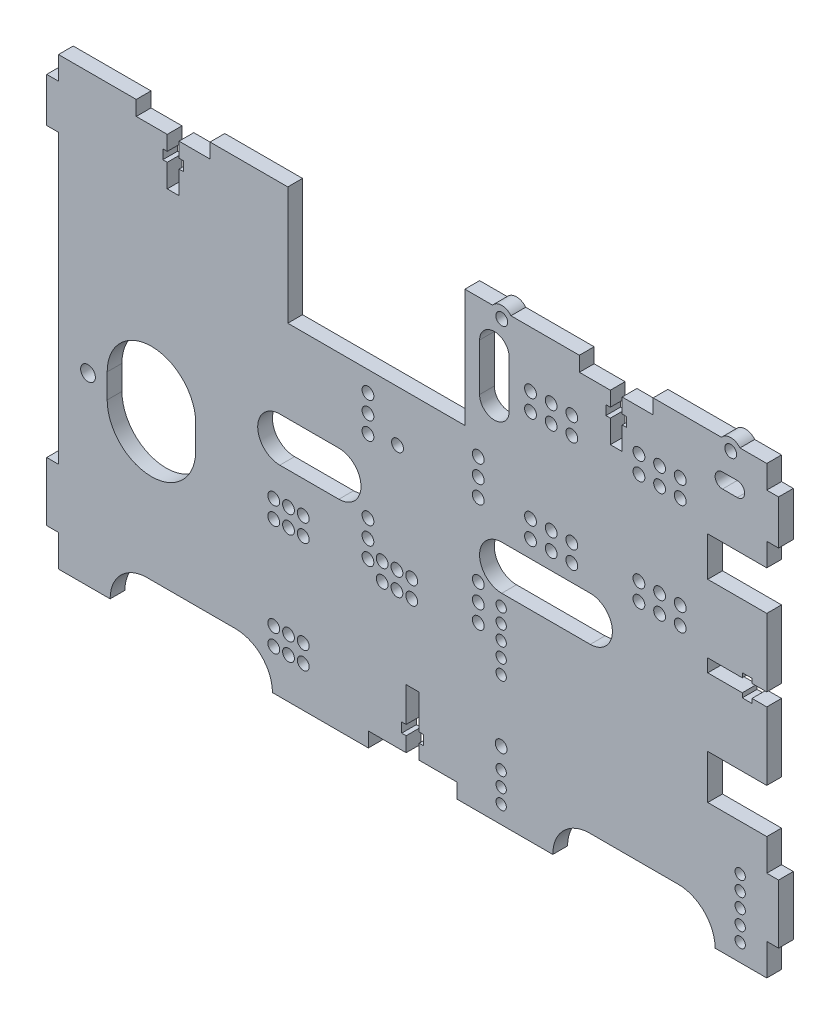
SolidWorks part; units mm, degrees
ref_plane "Front Plane" through (0, 0, 0) normal (0, 0, 1) x (1, 0, 0)
ref_plane "Top Plane" through (0, 0, 0) normal (0, 1, 0) x (1, 0, 0)
ref_plane "Right Plane" through (0, 0, 0) normal (1, 0, 0) x (0, 0, -1)
sketch "Sketch1" plane through (0, 0, 0) normal (0, 0, 1) x (1, 0, 0)
  line L1 (-120, 75.5) -> (120, 75.5)
  line L2 (-120, 75.5) -> (-120, -75.5)
  line L3 (-120, -75.5) -> (120, -75.5)
  line L4 (120, 75.5) -> (120, -75.5)
  dimension "D1" = 240
  dimension "D2" = 120
  dimension "D3" = 151
  dimension "D4" = 75.5
extrude "Boss-Extrude1" add sketch "Sketch1" along normal blind 5
sketch "Sketch2" plane through (0, 0, 0) normal (0, 0, -1) x (-1, 0, 0)
  line L1 (42.3015, 35.5) -> (42.3015, 75.5)
  line L3 (-17.6985, 75.5) -> (-17.6985, 35.5)
  line L4 (-120, 75.5) -> (120, 75.5) construction
  line L5 (42.3015, 35.5) -> (-17.6985, 35.5)
  line L6 (42.3015, 75.5) -> (-17.6985, 75.5)
  line L7 (-120, -75.5) -> (-120, 75.5) construction
  dimension "D1" = 60
  dimension "D2" = 102.3015
extrude "Cut-Extrude1" cut sketch "Sketch2" against normal blind 5
sketch "Sketch4" plane through (0, 0, 0) normal (0, 0, -1) x (-1, 0, 0)
  circle A0 centre (-107.8, 73) radius 2
  circle A1 centre (-30.2, 73) radius 2
  dimension "D1" = 4
  dimension "D2" = 4
extrude "Cut-Extrude3" cut sketch "Sketch4" against normal blind 5
sketch "Sketch5" plane through (0, 0, 0) normal (0, 0, -1) x (-1, 0, 0)
  circle A0 centre (-30.2, 73) radius 2
  circle A1 centre (-107.8, 73) radius 2
  circle A2 centre (-30.2, 73) radius 4
  circle A3 centre (-107.8, 73) radius 4
  dimension "D1" = 8
  dimension "D2" = 8
extrude "Boss-Extrude2" add sketch "Sketch5" against normal blind 5
sketch "Sketch6" plane through (0, 0, 0) normal (0, 0, -1) x (-1, 0, 0)
  circle A0 centre (117.5, 7.7) radius 2
  circle A1 centre (117.5, 63.3) radius 2
  dimension "D1" = 4
  dimension "D2" = 4
extrude "Cut-Extrude4" [suppressed] cut sketch "Sketch6" against normal blind 5
sketch "Sketch7" [suppressed] plane through (0, 0, 0) normal (0, 0, -1) x (-1, 0, 0)
  circle A0 centre (117.5, 7.7) radius 2
  circle A1 centre (117.5, 63.3) radius 1.9875
  circle A2 centre (117.5, 7.7) radius 4
  circle A3 centre (117.5, 63.3) radius 4
  dimension "D1" = 8
  dimension "D2" = 8
extrude "Boss-Extrude3" [suppressed] add sketch "Sketch7" against normal blind 5
sketch "Sketch8" plane through (0, 0, 0) normal (0, 0, -1) x (-1, 0, 0)
  line L0 (105, -60.5) -> (105, -40.5) construction
  line L1 (100, -60.5) -> (100, -40.5)
  line L2 (110, -60.5) -> (110, -40.5)
  line L3 (120, -75.5) -> (-120, -75.5) construction
  line L4 (120, 75.5) -> (120, -75.5) construction
  line L5 (0, 0) -> (0, -55.5387) construction
  arc A0 (100, -60.5) -> (110, -60.5) centre (105, -60.5) ccw
  arc A1 (110, -40.5) -> (100, -40.5) centre (105, -40.5) ccw
  point P2 (105, -50.5)
  point P17 (-92, -45.5)
  dimension "D1" = 20
  dimension "D2" = 15
  dimension "D3" = 10
  dimension "D4" = 10
extrude "Cut-Extrude5" [suppressed] cut sketch "Sketch8" against normal blind 5
sketch "Sketch9" plane through (0, 0, 0) normal (0, 0, -1) x (-1, 0, 0)
  circle A0 centre (117.5, 44.8) radius 2
  circle A1 centre (117.5, -10.8) radius 2
  dimension "D1" = 4
  dimension "D2" = 4
extrude "Cut-Extrude6" [suppressed] cut sketch "Sketch9" against normal blind 5
sketch "Sketch10" [suppressed] plane through (0, 0, 0) normal (0, 0, -1) x (-1, 0, 0)
  circle A0 centre (117.5, -10.8) radius 2
  circle A1 centre (117.5, -10.8) radius 4
  circle A2 centre (117.5, 44.8) radius 2
  circle A3 centre (117.5, 44.8) radius 4
  dimension "D1" = 8
  dimension "D2" = 8
extrude "Boss-Extrude4" [suppressed] add sketch "Sketch10" against normal blind 5
sketch "Sketch12" plane through (0, 0, 0) normal (0, 0, -1) x (-1, 0, 0)
  circle A0 centre (-28.1604, -53.4404) radius 2
  dimension "D1" = 4
extrude "Cut-Extrude7" [suppressed] cut sketch "Sketch12" against normal blind 5
sketch "Sketch13" plane through (0, 0, 0) normal (0, 0, -1) x (-1, 0, 0)
  circle A1 centre (110, -13) radius 2.5
extrude "Cut-Extrude8" cut sketch "Sketch13" against normal blind 10
sketch "Sketch14" plane through (0, 0, 0) normal (0, 0, -1) x (-1, 0, 0)
  line L0 (-104.6775, 75.5) -> (-33.3225, 75.5) construction
  line L1 (-120, -75.5) -> (-120, 75.5) construction
  line L2 (120, -75.5) -> (-120, -75.5) construction
  line L3 (120, 75.5) -> (120, -75.5) construction
  line L4 (42.3015, 75.5) -> (120, 75.5) construction
  circle A0 centre (-105, -60.5) radius 2.5
  circle A1 centre (105, -60.5) radius 2.5
  circle A2 centre (-105, 60.5) radius 2.5
  circle A3 centre (105, 60.5) radius 2.5
  dimension "D1" = 5
  dimension "D2" = 5
  dimension "D3" = 5
  dimension "D4" = 5
  dimension "D5" = 15
  dimension "D6" = 15
  dimension "D7" = 15
  dimension "D8" = 15
  dimension "D9" = 15
  dimension "D10" = 15
  dimension "D11" = 15
  dimension "D12" = 15
extrude "Cut-Extrude9" [suppressed] cut sketch "Sketch14" against normal blind 10
sketch "Sketch15" plane through (0, 0, 0) normal (0, 0, -1) x (-1, 0, 0)
  line L0 (-70, 0) -> (-50, 0) construction
  line L1 (-70, 7.5) -> (-50, 7.5)
  line L2 (-70, -7.5) -> (-50, -7.5)
  line L3 (50, 0) -> (70, 0) construction
  line L4 (50, 7.5) -> (70, 7.5)
  line L5 (50, -7.5) -> (70, -7.5)
  line L6 (-102.5, 55.5) -> (-102.5, 35.5) construction
  line L7 (-95, 55.5) -> (-95, 35.5)
  line L8 (-110, 55.5) -> (-110, 35.5)
  line L9 (-104.6775, 75.5) -> (-33.3225, 75.5) construction
  line L10 (-120, -75.5) -> (-120, 75.5) construction
  line L11 (0, 0) -> (0, 86.6929) construction
  line L12 (102.5, 55.5) -> (102.5, 35.5) construction
  line L13 (95, 55.5) -> (95, 35.5)
  line L14 (110, 55.5) -> (110, 35.5)
  arc A0 (-70, 7.5) -> (-70, -7.5) centre (-70, 0) ccw
  arc A1 (-50, -7.5) -> (-50, 7.5) centre (-50, 0) ccw
  arc A2 (50, 7.5) -> (50, -7.5) centre (50, 0) ccw
  arc A3 (70, -7.5) -> (70, 7.5) centre (70, 0) ccw
  arc A4 (-95, 55.5) -> (-110, 55.5) centre (-102.5, 55.5) ccw
  arc A5 (-110, 35.5) -> (-95, 35.5) centre (-102.5, 35.5) ccw
  arc A6 (95, 55.5) -> (110, 55.5) centre (102.5, 55.5) cw
  arc A7 (110, 35.5) -> (95, 35.5) centre (102.5, 35.5) cw
  point P2 (-60, 0)
  point P7 (60, 0)
  point P14 (-60, 7.5)
  point P15 (60, -7.5)
  point P16 (-102.5, 45.5)
  point P32 (102.5, 45.5)
  dimension "D1" = 20
  dimension "D2" = 20
  dimension "D3" = 50
  dimension "D4" = 50
  dimension "D5" = 15
  dimension "D6" = 15
  dimension "D7" = 15
  dimension "D8" = 20
  dimension "D9" = 20
  dimension "D10" = 10
extrude "Cut-Extrude10" [suppressed] cut sketch "Sketch15" against normal blind 10
sketch "Sketch16" plane through (0, 0, 0) normal (0, 0, -1) x (-1, 0, 0)
  line L0 (-120, -75.5) -> (-120, 75.5) construction
  line L9 (-120, 67.675) -> (-124, 67.675)
  line L10 (-120, 67.675) -> (-120, 52.675)
  line L11 (-120, 52.675) -> (-124, 52.675)
  line L12 (-124, 67.675) -> (-124, 52.675)
  line L13 (-120, -64.75) -> (-124, -64.75)
  line L14 (-120, -64.75) -> (-120, -44.75)
  line L15 (-120, -44.75) -> (-124, -44.75)
  line L16 (-124, -64.75) -> (-124, -44.75)
  line L18 (-120, 75.5) -> (-110.9225, 75.5) construction
  line L19 (120, -75.5) -> (-120, -75.5) construction
  line L20 (0, 0) -> (0, -42.8978) construction
  line L21 (124, -64.75) -> (124, -44.75)
  line L22 (120, -44.75) -> (124, -44.75)
  line L23 (120, -64.75) -> (120, -44.75)
  line L24 (120, -64.75) -> (124, -64.75)
  line L25 (124, 67.675) -> (124, 52.675)
  line L26 (120, 52.675) -> (124, 52.675)
  line L27 (120, 67.675) -> (120, 52.675)
  line L28 (120, 67.675) -> (124, 67.675)
  dimension "D1" = 7.825
  dimension "D2" = 15
  dimension "D3" = 4
  dimension "D4" = 10.75
  dimension "D5" = 20
  dimension "D6" = 4
extrude "Boss-Extrude5" add sketch "Sketch16" against normal blind 5
sketch "Sketch18" plane through (0, 0, 0) normal (0, 0, -1) x (-1, 0, 0)
  line L1 (-77.45, -55.5) -> (-77.45, -75.5)
  line L3 (57.85, -75.5) -> (57.85, -55.5)
  line L5 (-77.45, -55.5) -> (57.85, -55.5)
  line L7 (-77.45, -75.5) -> (57.85, -75.5)
  line L8 (120, -65.5) -> (120, -75.5) construction
  line L9 (-120, -75.5) -> (-120, -65.5) construction
  line L10 (120, -75.5) -> (-120, -75.5) construction
  point P8 (120, -70.5)
  dimension "D1" = 62.15
  dimension "D2" = 42.55
  dimension "D3" = 20
extrude "Cut-Extrude13" [suppressed] cut sketch "Sketch18" against normal blind 10
sketch "Sketch19" [suppressed] plane through (0, 0, 0) normal (0, 0, -1) x (-1, 0, 0)
  circle A0 centre (-28.1604, -53.4404) radius 2
  circle A1 centre (-28.1604, -53.4404) radius 4
  dimension "D1" = 8
extrude "Boss-Extrude6" [suppressed] add sketch "Sketch19" against normal blind 5
sketch "Sketch20" [suppressed] plane through (0, 0, 0) normal (0, 0, -1) x (-1, 0, 0)
  line L4 (57.85, -70.5) -> (57.85, -75.5)
  line L5 (57.85, -75.5) -> (82.65, -75.5)
  line L6 (82.65, -70.5) -> (82.65, -75.5)
  line L7 (57.85, -70.5) -> (82.65, -70.5)
  line L9 (57.85, -75.5) -> (57.85, -55.5) construction
  line L10 (120, -55.5) -> (120, -75.5) construction
  dimension "D1" = 37.35
extrude "Cut-Extrude14" [suppressed] cut sketch "Sketch20" against normal blind 5
sketch "Sketch21" [suppressed] plane through (0, 0, 0) normal (0, 0, -1) x (-1, 0, 0)
  line L0 (-120, -75.5) -> (-120, -55.5) construction
  line L1 (-77.45, -55.5) -> (-77.45, -75.5) construction
  line L8 (-102.45, -75.5) -> (-77.45, -75.5)
  line L9 (-102.45, -70.5) -> (-102.45, -75.5)
  line L10 (-77.45, -70.5) -> (-102.45, -70.5)
  line L11 (-77.45, -75.5) -> (-77.45, -70.5)
  dimension "D1" = 17.55
extrude "Cut-Extrude15" [suppressed] cut sketch "Sketch21" against normal blind 5
sketch "Sketch22" [suppressed] plane through (0, 0, 0) normal (0, 0, -1) x (-1, 0, 0)
  line L0 (68.25, -55.5) -> (68.25, -62.2)
  line L1 (82.65, -70.5) -> (57.85, -70.5) construction
  line L2 (68.25, -55.5) -> (72.65, -55.5)
  line L3 (72.65, -55.5) -> (72.65, -62.2)
  line L4 (72.65, -62.2) -> (74.15, -62.2)
  line L5 (74.15, -62.2) -> (74.15, -65.5)
  line L6 (74.15, -65.5) -> (72.65, -65.5)
  line L7 (72.65, -65.5) -> (72.65, -70.5)
  line L8 (68.25, -62.2) -> (66.75, -62.2)
  line L9 (66.75, -62.2) -> (66.75, -65.5)
  line L10 (66.75, -65.5) -> (68.25, -65.5)
  line L11 (68.25, -65.5) -> (68.25, -70.5)
  line L12 (68.25, -70.5) -> (72.65, -70.5)
  line L13 (70.45, -70.5) -> (70.45, -45.2903) construction
  line L14 (-92.45, -55.5) -> (-92.45, -62.2)
  line L15 (-92.45, -55.5) -> (-88.05, -55.5)
  line L16 (-88.05, -55.5) -> (-88.05, -62.2)
  line L17 (-88.05, -62.2) -> (-86.55, -62.2)
  line L18 (-86.55, -62.2) -> (-86.55, -65.5)
  line L19 (-86.55, -65.5) -> (-88.05, -65.5)
  line L20 (-88.05, -65.5) -> (-88.05, -70.5)
  line L21 (-92.45, -62.2) -> (-93.95, -62.2)
  line L22 (-93.95, -62.2) -> (-93.95, -65.5)
  line L23 (-93.95, -65.5) -> (-92.45, -65.5)
  line L24 (-92.45, -65.5) -> (-92.45, -70.5)
  line L25 (-92.45, -70.5) -> (-88.05, -70.5)
  line L26 (-90.25, -70.5) -> (-90.25, -50.7904) construction
  line L27 (-77.45, -70.5) -> (-102.45, -70.5) construction
  line L28 (82.65, -75.5) -> (82.65, -70.5) construction
  line L29 (-102.45, -70.5) -> (-102.45, -75.5) construction
  dimension "D1" = 4.4
  dimension "D2" = 1.5
  dimension "D3" = 3.3
  dimension "D4" = 5
  dimension "D5" = 15
  dimension "D6" = 4.4
  dimension "D7" = 1.5
  dimension "D8" = 3.3
  dimension "D9" = 15
  dimension "D10" = 5
  dimension "D11" = 10
  dimension "D12" = 10
extrude "Cut-Extrude16" [suppressed] cut sketch "Sketch22" against normal blind 5
sketch "Sketch23" plane through (0, 0, 0) normal (0, 0, -1) x (-1, 0, 0)
  line L0 (-107.5, 60.5) -> (-107.5, 40.5) construction
  line L1 (-100, 60.5) -> (-100, 40.5)
  line L2 (-115, 60.5) -> (-115, 40.5)
  line L3 (-120, 67.675) -> (-120, 75.5) construction
  line L4 (-104.6775, 75.5) -> (-33.3225, 75.5) construction
  line L5 (0, 0) -> (0, 68.359) construction
  line L6 (107.5, 60.5) -> (107.5, 40.5) construction
  line L7 (100, 60.5) -> (100, 40.5)
  line L8 (115, 60.5) -> (115, 40.5)
  arc A0 (-100, 60.5) -> (-115, 60.5) centre (-107.5, 60.5) ccw
  arc A1 (-115, 40.5) -> (-100, 40.5) centre (-107.5, 40.5) ccw
  arc A2 (100, 60.5) -> (115, 60.5) centre (107.5, 60.5) cw
  arc A3 (115, 40.5) -> (100, 40.5) centre (107.5, 40.5) cw
  point P0 (-107.5, 50.5)
  point P16 (107.5, 50.5)
  dimension "D1" = 15
  dimension "D2" = 20
  dimension "D3" = 5
  dimension "D4" = 15
extrude "Cut-Extrude17" [suppressed] cut sketch "Sketch23" against normal blind 10
sketch "Sketch24" plane through (0, 0, 0) normal (0, 0, -1) x (-1, 0, 0)
  circle A0 centre (-30, -52.5) radius 2
  circle A1 centre (5.1152, 18.2667) radius 2
  dimension "D1" = 4
  dimension "D2" = 4
extrude "Cut-Extrude18" cut sketch "Sketch24" against normal blind 10
sketch "Sketch25" plane through (0, 0, 0) normal (0, 0, -1) x (-1, 0, 0)
  circle A0 centre (-30, -52.5) radius 2
  circle A1 centre (-30, -52.5) radius 4
  dimension "D1" = 8
extrude "Boss-Extrude7" add sketch "Sketch25" against normal blind 5
sketch "Sketch26" plane through (0, 0, 0) normal (0, 0, -1) x (-1, 0, 0)
  line L0 (-120, -44.75) -> (-120, 52.675) construction
  line L1 (-120, -19) -> (-100, -19)
  line L2 (-120, -19) -> (-120, -34)
  line L3 (-120, -34) -> (-100, -34)
  line L4 (-100, -19) -> (-100, -34)
  line L5 (-120, 44.85) -> (-100, 44.85)
  line L6 (-120, 44.85) -> (-120, 31.5)
  line L7 (-120, 31.5) -> (-100, 31.5)
  line L8 (-100, 44.85) -> (-100, 31.5)
  line L9 (-120, -44.75) -> (-120, 52.675) construction
  line L10 (120, -75.5) -> (-120, -75.5) construction
  dimension "D1" = 13.35
  dimension "D2" = 15
  dimension "D3" = 41.5
  dimension "D4" = 50.5
  dimension "D5" = 20
extrude "Cut-Extrude19" cut sketch "Sketch26" against normal blind 10
sketch "Sketch27" plane through (0, 0, 0) normal (0, 0, -1) x (-1, 0, 0)
  line L0 (-120, 8.45) -> (-115, 8.45)
  line L1 (-115, 8.45) -> (-115, 9.95)
  line L2 (-115, 9.95) -> (-111.7, 9.95)
  line L3 (-111.7, 9.95) -> (-111.7, 8.45)
  line L4 (-111.7, 8.45) -> (-100, 8.45)
  line L5 (-100, 8.45) -> (-100, 4.05)
  line L6 (-100, 4.05) -> (-111.7, 4.05)
  line L7 (-111.7, 4.05) -> (-111.7, 2.55)
  line L8 (-111.7, 2.55) -> (-115, 2.55)
  line L9 (-115, 2.55) -> (-115, 4.05)
  line L10 (-115, 4.05) -> (-120, 4.05)
  line L11 (-120, 4.05) -> (-120, 8.45)
  line L12 (-120, -19) -> (-120, 31.5) construction
  line L13 (-100, -19) -> (-120, -19) construction
  dimension "D1" = 4.4
  dimension "D2" = 1.5
  dimension "D3" = 3.3
  dimension "D4" = 5
  dimension "D5" = 20
  dimension "D6" = 1.5
  dimension "D7" = 23.05
extrude "Cut-Extrude20" cut sketch "Sketch27" against normal blind 10
sketch "Sketch29" plane through (0, 0, 0) normal (0, 0, -1) x (-1, 0, 0)
  line L0 (60, -75.5) -> (90, -75.5) construction
  line L1 (120, -75.5) -> (-120, -75.5) construction
  line L2 (60, -63) -> (90, -63)
  line L3 (60, -88) -> (90, -88)
  line L4 (-90, -75.5) -> (-60, -75.5) construction
  line L5 (-90, -63) -> (-60, -63)
  line L6 (-90, -88) -> (-60, -88)
  line L7 (-120, -75.5) -> (-120, -64.75) construction
  line L8 (120, -64.75) -> (120, -75.5) construction
  line L9 (0, 0) -> (0, -112.4196) construction
  arc A0 (60, -63) -> (60, -88) centre (60, -75.5) ccw
  arc A1 (90, -88) -> (90, -63) centre (90, -75.5) ccw
  arc A2 (-90, -63) -> (-90, -88) centre (-90, -75.5) ccw
  arc A3 (-60, -88) -> (-60, -63) centre (-60, -75.5) ccw
  point P4 (75, -75.5)
  point P9 (-75, -75.5)
  point P20 (75, -88)
  dimension "D1" = 30
  dimension "D2" = 30
  dimension "D3" = 30
  dimension "D4" = 30
  dimension "D5" = 25
  dimension "D6" = 25
extrude "Cut-Extrude24" cut sketch "Sketch29" against normal blind 5
sketch "Sketch31" plane through (0, 0, 0) normal (0, 0, -1) x (-1, 0, 0)
  line L0 (47.5, -75.5) -> (-47.5, -75.5) construction
  line L1 (-15, -75.5) -> (15, -75.5)
  line L2 (-15, -75.5) -> (-15, -70.5)
  line L3 (-15, -70.5) -> (15, -70.5)
  line L4 (15, -75.5) -> (15, -70.5)
  line L5 (-120, -75.5) -> (-120, -64.75) construction
  point P6 (0, -75.5)
  dimension "D3" = 105
  dimension "D1" = 30
  dimension "D2" = 5
extrude "Cut-Extrude25" cut sketch "Sketch31" against normal blind 5
sketch "Sketch32" plane through (0, 0, 0) normal (0, 0, -1) x (-1, 0, 0)
  line L0 (-2.2, -50.5) -> (-2.2, -62.2)
  line L1 (-2.2, -50.5) -> (2.2, -50.5)
  line L2 (2.2, -50.5) -> (2.2, -62.2)
  line L3 (2.2, -62.2) -> (3.7, -62.2)
  line L4 (3.7, -62.2) -> (3.7, -65.5)
  line L5 (3.7, -65.5) -> (2.2, -65.5)
  line L6 (2.2, -65.5) -> (2.2, -70.5)
  line L7 (-2.2, -62.2) -> (-3.7, -62.2)
  line L8 (-3.7, -62.2) -> (-3.7, -65.5)
  line L9 (-3.7, -65.5) -> (-2.2, -65.5)
  line L10 (-2.2, -65.5) -> (-2.2, -70.5)
  line L11 (-2.2, -70.5) -> (2.2, -70.5)
  line L12 (0, -70.5) -> (0, -36.0653) construction
  line L13 (15, -70.5) -> (-15, -70.5) construction
  line L14 (-15, -70.5) -> (-15, -75.5) construction
  dimension "D1" = 4.4
  dimension "D2" = 1.5
  dimension "D3" = 3.3
  dimension "D4" = 20
  dimension "D5" = 12.8
extrude "Cut-Extrude26" cut sketch "Sketch32" against normal blind 5
sketch "Sketch34" plane through (0, 0, 0) normal (0, 0, -1) x (-1, 0, 0)
  line L2 (88.5, -17.623) -> (88.5, -9.377) construction
  line L3 (73.5, -17.623) -> (73.5, -9.377)
  line L4 (103.5, -17.623) -> (103.5, -9.377)
  arc A5 (73.5, -17.623) -> (103.5, -17.623) centre (88.5, -17.623) ccw
  arc A6 (103.5, -9.377) -> (73.5, -9.377) centre (88.5, -9.377) ccw
  point P18 (88.5, -13.5)
  point P32 (103.5, -13.5)
  dimension "D1" = 30
extrude "Cut-Extrude27" cut sketch "Sketch34" against normal blind 5
sketch "Sketch35" plane through (0, 0, 0) normal (0, 0, -1) x (-1, 0, 0)
  line L0 (-27.6985, 63.0722) -> (-27.6985, 47.0722) construction
  line L1 (-22.6985, 63.0722) -> (-22.6985, 47.0722)
  line L2 (-32.6985, 63.0722) -> (-32.6985, 47.0722)
  line L7 (-17.6985, 75.5) -> (-17.6985, 35.5) construction
  arc A0 (-22.6985, 63.0722) -> (-32.6985, 63.0722) centre (-27.6985, 63.0722) ccw
  arc A1 (-32.6985, 47.0722) -> (-22.6985, 47.0722) centre (-27.6985, 47.0722) ccw
  point P2 (-27.6985, 55.0722)
  point P7 (-72, 65.5)
  point P14 (-32.6985, 55.0722)
  dimension "D4" = 16
  dimension "D2" = 10
  dimension "D6" = 5
extrude "Cut-Extrude28" cut sketch "Sketch35" against normal blind 10
sketch "Sketch37" plane through (0, 0, 0) normal (0, 0, -1) x (-1, 0, 0)
  line L0 (-120, -75.5) -> (-120, -64.75) construction
  circle A0 centre (-111, -59.5) radius 1.75
  circle A1 centre (-30, -59.5) radius 1.75
  arc A3 (-90, -63) -> (-102.5, -75.5) centre (-90, -75.5) ccw construction
  circle A4 centre (-30, -21.5) radius 1.75
  circle A5 centre (-30, -16.5) radius 1.75
  circle A7 centre (-111, -54.5) radius 1.75
  circle A8 centre (-30, -11.5) radius 1.75
  circle A10 centre (-111, -49.5) radius 1.75
  circle A11 centre (-30, -49.5) radius 1.75 [skipped]
  circle A12 centre (-30, -54.5) radius 1.75 [skipped]
  circle A27 centre (-111, -64.5) radius 1.75
  circle A28 centre (-30, -64.5) radius 1.75
  circle A29 centre (-30, -26.5) radius 1.75
  circle A30 centre (-111, -69.5) radius 1.75
  circle A31 centre (-30, -69.5) radius 1.75
  circle A32 centre (-30, -31.5) radius 1.75
  dimension "D3" = 3.5
  dimension "D4" = 81
  dimension "D5" = 3.5
  dimension "D6" = 3
  dimension "D8" = 3.5
  dimension "D1" = 16
  dimension "D2" = 9
  dimension "D7" = 3
sketch "Sketch38" plane through (0, 0, 0) normal (0, 0, -1) x (-1, 0, 0)
  line L0 (45, 0) -> (25, 0) construction
  line L1 (45, -7.5) -> (25, -7.5)
  line L2 (45, 7.5) -> (25, 7.5)
  line L3 (-60.1894, 0) -> (-30.1894, 0) construction
  line L4 (-60.1894, 7.5) -> (-30.1894, 7.5)
  line L5 (-60.1894, -7.5) -> (-30.1894, -7.5)
  arc A0 (45, -7.5) -> (45, 7.5) centre (45, 0) ccw
  arc A1 (25, 7.5) -> (25, -7.5) centre (25, 0) ccw
  arc A2 (-60.1894, 7.5) -> (-60.1894, -7.5) centre (-60.1894, 0) ccw
  arc A3 (-30.1894, -7.5) -> (-30.1894, 7.5) centre (-30.1894, 0) ccw
  point P3 (35, 0)
  point P10 (-45.1894, 0)
  point P15 (-45.1894, -7.5)
  dimension "D1" = 25
  dimension "D2" = 15
  dimension "D3" = 15
  dimension "D4" = 30
  dimension "D5" = 20
extrude "Cut-Extrude30" cut sketch "Sketch38" against normal blind 10
sketch "Sketch39" plane through (0, 0, 0) normal (0, 0, -1) x (-1, 0, 0)
  line L0 (-110, 63) -> (-105, 63) construction
  line L1 (-110, 65.5) -> (-105, 65.5)
  line L2 (-110, 60.5) -> (-105, 60.5)
  line L3 (-120, 44.85) -> (-120, 52.675) construction
  line L4 (-104.6775, 75.5) -> (-33.3225, 75.5) construction
  arc A0 (-110, 65.5) -> (-110, 60.5) centre (-110, 63) ccw
  arc A1 (-105, 60.5) -> (-105, 65.5) centre (-105, 63) ccw
  point P2 (-107.5, 63)
  dimension "D1" = 10
  dimension "D2" = 5
  dimension "D3" = 5
  dimension "D4" = 10
extrude "Cut-Extrude31" cut sketch "Sketch39" against normal blind 10
sketch "Sketch40" plane through (0, 0, 0) normal (0, 0, -1) x (-1, 0, 0)
  circle A0 centre (-46.9439, 56.6363) radius 2
  circle A1 centre (-83.6857, 19.2568) radius 2
  circle A2 centre (-46.9439, 19.2568) radius 2
  circle A3 centre (-83.6857, 56.6363) radius 2
  circle A4 centre (-53.9439, 56.6363) radius 2
  circle A5 centre (-90.6857, 19.2568) radius 2
  circle A6 centre (-53.9439, 19.2568) radius 2
  circle A7 centre (-90.6857, 56.6363) radius 2
  circle A8 centre (-46.9439, 50.6363) radius 2
  circle A9 centre (-83.6857, 13.2568) radius 2
  circle A10 centre (-46.9439, 13.2568) radius 2
  circle A11 centre (-83.6857, 50.6363) radius 2
  circle A12 centre (-53.9439, 50.6363) radius 2
  circle A13 centre (-90.6857, 13.2568) radius 2
  circle A14 centre (-53.9439, 13.2568) radius 2
  circle A15 centre (-90.6857, 50.6363) radius 2
  circle A16 centre (-39.9439, 50.6363) radius 2
  circle A17 centre (-76.6857, 13.2568) radius 2
  circle A18 centre (-39.9439, 13.2568) radius 2
  circle A19 centre (-76.6857, 50.6363) radius 2
  circle A20 centre (-22.2432, 22.5943) radius 2
  circle A21 centre (15.1363, 22.5943) radius 2
  circle A44 centre (-76.6857, 56.6363) radius 2
  circle A45 centre (-39.9439, 56.6363) radius 2
  circle A46 centre (-22.2432, 28.5943) radius 2
  circle A47 centre (-39.9439, 19.2568) radius 2
  circle A48 centre (15.1363, 28.5943) radius 2
  circle A49 centre (15.1363, -8.1475) radius 2
  circle A50 centre (37.0561, -18.3637) radius 2
  circle A51 centre (0.3143, -18.3637) radius 2
  circle A53 centre (-76.6857, 19.2568) radius 2
  circle A54 centre (-22.2432, -8.1475) radius 2
  circle A55 centre (37.0561, -55.7432) radius 2
  circle A56 centre (15.1363, -14.1475) radius 2
  circle A57 centre (-22.2432, -14.1475) radius 2
  circle A58 centre (-22.2432, 16.5943) radius 2
  circle A59 centre (15.1363, 16.5943) radius 2
  circle A60 centre (15.1363, -20.1475) radius 2
  circle A61 centre (-22.2432, -20.1475) radius 2
  circle A62 centre (42.0561, -18.3637) radius 2
  circle A63 centre (42.0561, -55.7432) radius 2
  circle A64 centre (5.3143, -18.3637) radius 2
  circle A65 centre (47.0561, -18.3637) radius 2
  circle A66 centre (47.0561, -55.7432) radius 2
  circle A67 centre (10.3143, -18.3637) radius 2
  circle A68 centre (42.0561, -24.3637) radius 2
  circle A69 centre (42.0561, -61.7432) radius 2
  circle A70 centre (5.3143, -24.3637) radius 2
  circle A71 centre (47.0561, -24.3637) radius 2
  circle A72 centre (47.0561, -61.7432) radius 2
  circle A73 centre (10.3143, -24.3637) radius 2
  circle A74 centre (37.0561, -24.3637) radius 2
  circle A75 centre (37.0561, -61.7432) radius 2
  circle A76 centre (0.3143, -24.3637) radius 2
  dimension "D1" = 4
  dimension "D2" = 4
  dimension "D3" = 4
  dimension "D4" = 4
  dimension "D5" = 4
  dimension "D6" = 4
  dimension "D7" = 4
  dimension "D8" = 4
  dimension "D9" = 4
  dimension "D10" = 4
  dimension "D11" = 4
  dimension "D12" = 3
  dimension "D13" = 2
  dimension "D14" = 3
  dimension "D15" = 3
  dimension "D16" = 2
extrude "Cut-Extrude32" cut sketch "Sketch40" against normal blind 10
extrude "Cut-Extrude34" cut sketch "Sketch37" against normal blind 5
sketch "Sketch41" plane through (0, 0, 0) normal (0, 0, -1) x (-1, 0, 0)
  line L0 (80, 60.5) -> (100, 60.5) construction
  line L1 (80, 65.5) -> (100, 65.5)
  line L2 (80, 55.5) -> (100, 55.5)
  line L3 (120, 75.5) -> (120, 67.675) construction
  line L4 (42.3015, 75.5) -> (120, 75.5) construction
  arc A0 (80, 65.5) -> (80, 55.5) centre (80, 60.5) ccw
  arc A1 (100, 55.5) -> (100, 65.5) centre (100, 60.5) ccw
  point P2 (90, 60.5)
  dimension "D1" = 20
  dimension "D2" = 10
  dimension "D3" = 10
  dimension "D4" = 20
extrude "Cut-Extrude35" [suppressed] cut sketch "Sketch41" against normal blind 10
sketch "Sketch44" plane through (0, 0, 0) normal (0, 0, -1) x (-1, 0, 0)
  line L1 (-56.5, 75.5) -> (-81.5, 75.5)
  line L2 (-56.5, 75.5) -> (-56.5, 70.5)
  line L3 (-56.5, 70.5) -> (-81.5, 70.5)
  line L4 (-81.5, 75.5) -> (-81.5, 70.5)
extrude "Cut-Extrude38" cut sketch "Sketch44" against normal blind 10
sketch "Sketch45" plane through (0, 0, 0) normal (0, 0, -1) x (-1, 0, 0)
  line L0 (-69, 70.5) -> (-69, 62.3478) construction
  line L1 (-81.5, 70.5) -> (-56.5, 70.5) construction
  line L2 (-67, 70.5) -> (-71, 70.5)
  line L3 (-71, 70.5) -> (-71, 65.5)
  line L4 (-71, 65.5) -> (-72.5, 65.5)
  line L5 (-72.5, 65.5) -> (-72.5, 62.3)
  line L6 (-72.5, 62.3) -> (-71, 62.3)
  line L7 (-71, 62.3) -> (-71, 54.5)
  line L8 (-71, 54.5) -> (-67, 54.5)
  line L9 (-67, 54.5) -> (-67, 62.3)
  line L10 (-67, 62.3) -> (-65.5, 62.3)
  line L11 (-65.5, 62.3) -> (-65.5, 65.5)
  line L12 (-65.5, 65.5) -> (-67, 65.5)
  line L13 (-67, 65.5) -> (-67, 70.5)
  dimension "D1" = 2
  dimension "D2" = 5
  dimension "D3" = 3.2
  dimension "D4" = 2
  dimension "D5" = 1.5
  dimension "D6" = 1.5
  dimension "D7" = 16
extrude "Cut-Extrude39" cut sketch "Sketch45" against normal blind 5
sketch "Sketch46" plane through (0, 0, 0) normal (0, 0, -1) x (-1, 0, 0)
  line L0 (42.3015, 75.5) -> (120, 75.5) construction
  line L1 (68.6515, 75.5) -> (93.6515, 75.5)
  line L2 (68.6515, 75.5) -> (68.6515, 70.5)
  line L3 (68.6515, 70.5) -> (93.6515, 70.5)
  line L4 (93.6515, 75.5) -> (93.6515, 70.5)
  line L5 (42.3015, 35.5) -> (42.3015, 75.5) construction
  dimension "D1" = 26.35
  dimension "D2" = 5
  dimension "D3" = 25
extrude "Cut-Extrude40" cut sketch "Sketch46" against normal blind 10
sketch "Sketch47" plane through (0, 0, 0) normal (0, 0, -1) x (-1, 0, 0)
  line L0 (81.1515, 70.5) -> (81.1515, 62.3478) construction
  line L1 (83.1515, 70.5) -> (79.1515, 70.5)
  line L2 (79.1515, 70.5) -> (79.1515, 65.5)
  line L3 (79.1515, 65.5) -> (77.6515, 65.5)
  line L4 (77.6515, 65.5) -> (77.6515, 62.3)
  line L5 (77.6515, 62.3) -> (79.1515, 62.3)
  line L6 (79.1515, 62.3) -> (79.1515, 54.5)
  line L7 (79.1515, 54.5) -> (83.1515, 54.5)
  line L8 (83.1515, 54.5) -> (83.1515, 62.3)
  line L9 (83.1515, 62.3) -> (84.6515, 62.3)
  line L10 (84.6515, 62.3) -> (84.6515, 65.5)
  line L11 (84.6515, 65.5) -> (83.1515, 65.5)
  line L12 (83.1515, 65.5) -> (83.1515, 70.5)
  line L13 (68.6515, 70.5) -> (93.6515, 70.5) construction
  line L14 (93.6515, 70.5) -> (93.6515, 75.5) construction
  dimension "D1" = 2
  dimension "D2" = 5
  dimension "D3" = 3.2
  dimension "D4" = 2
  dimension "D5" = 1.5
  dimension "D6" = 1.5
  dimension "D7" = 16
  dimension "D8" = 12.5
extrude "Cut-Extrude41" cut sketch "Sketch47" against normal blind 10
